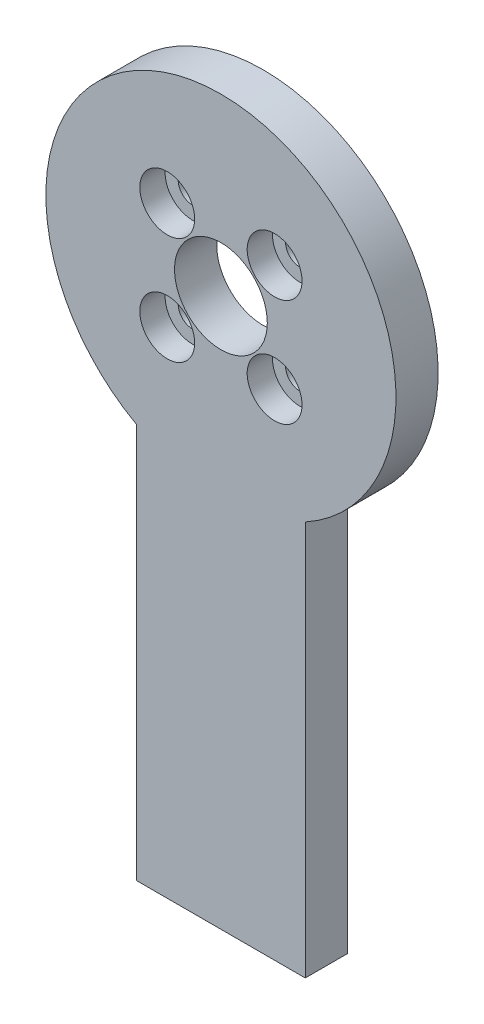
SolidWorks part; units mm, degrees
material "Сплав 2024"
ref_plane "Спереди" through (0, 0, 0) normal (0, 0, 1) x (1, 0, 0)
ref_plane "Сверху" through (0, 0, 0) normal (0, 1, 0) x (1, 0, 0)
ref_plane "Справа" through (0, 0, 0) normal (1, 0, 0) x (0, 0, -1)
sketch "Эскиз1" plane through (0, 0, 0) normal (0, 0, 1) x (1, 0, 0)
  circle A0 centre (0, 0) radius 20.75
  dimension "D1" = 41.5
extrude "Бобышка-Вытянуть1" add sketch "Эскиз1" along normal blind 5
sketch "Эскиз2" plane through (0, 0, 5) normal (0, 0, 1) x (1, 0, 0)
  line L0 (18.9835, 18.9835) -> (-18.9835, -18.9835) construction
  line L1 (-15.9524, 15.9524) -> (15.9524, -15.9524) construction
  line L2 (21.4819, 0) -> (-26.5434, 0) construction
  circle A0 centre (0, 0) radius 9 construction
  dimension "D1" = 18
  dimension "D2" = 45
hole_wizard "Цековка для винта с внутренним шестигранником M31" positions "Эскиз4" profile "Эскиз3" counterbore size "M3" standard "Ansi Metric" end condition through all
sketch "Эскиз4" plane through (0, 0, 5) normal (0, 0, 1) x (1, 0, 0)
  line L0 (-15.9524, 15.9524) -> (15.9524, -15.9524) construction
  line L1 (18.9835, 18.9835) -> (-18.9835, -18.9835) construction
  circle A0 centre (0, 0) radius 9 construction
  point P0 (-6.364, 6.364)
  point P6 (6.364, 6.364)
  point P10 (6.364, -6.364)
  point P12 (-6.364, -6.364)
sketch "Эскиз3" plane through (-6.364, 6.364, 5) normal (1, 0, 0) x (0, -1, 0)
  line L0 (0, 0) -> (0, 5)
  line L1 (0, 5) -> (1.7, 5)
  line L3 (1.7, 5) -> (1.7, 3)
  line L4 (1.7, 3) -> (3.25, 3)
  line L5 (3.25, 3) -> (3.25, 0)
  line L7 (3.25, 0) -> (0, 0)
  line L11 (0, -6.35) -> (0, 107.95) construction
  dimension "Диаметр сквозного отверстия" = 3.4
  dimension "Глубина сквозного отверстия" = 5
  dimension "Диаметр цековки" = 6.5
  dimension "Глубина цековки" = 3
sketch "Эскиз5" plane through (0, 0, 5) normal (0, 0, 1) x (1, 0, 0)
  circle A0 centre (0, 0) radius 5.5
  dimension "D1" = 11
extrude "Вырез-Вытянуть1" cut sketch "Эскиз5" against normal through all
sketch "Эскиз6" plane through (0, 0, 5) normal (0, 0, 1) x (1, 0, 0)
  line L0 (0, 4.9294) -> (0, -83.2905) construction
  line L2 (-10, -15) -> (10, -15)
  line L3 (-10, -15) -> (-10, -65)
  line L4 (-10, -65) -> (10, -65)
  line L5 (10, -15) -> (10, -65)
  line L6 (-10, -15) -> (10, -65) construction
  line L7 (-10, -65) -> (10, -15) construction
  point P4 (0, -40)
  dimension "D1" = 20
  dimension "D2" = 25
  dimension "D3" = 40
extrude "Бобышка-Вытянуть2" add sketch "Эскиз6" against normal up to surface (5 mm away) up to face at (5.5, 0, 0)
